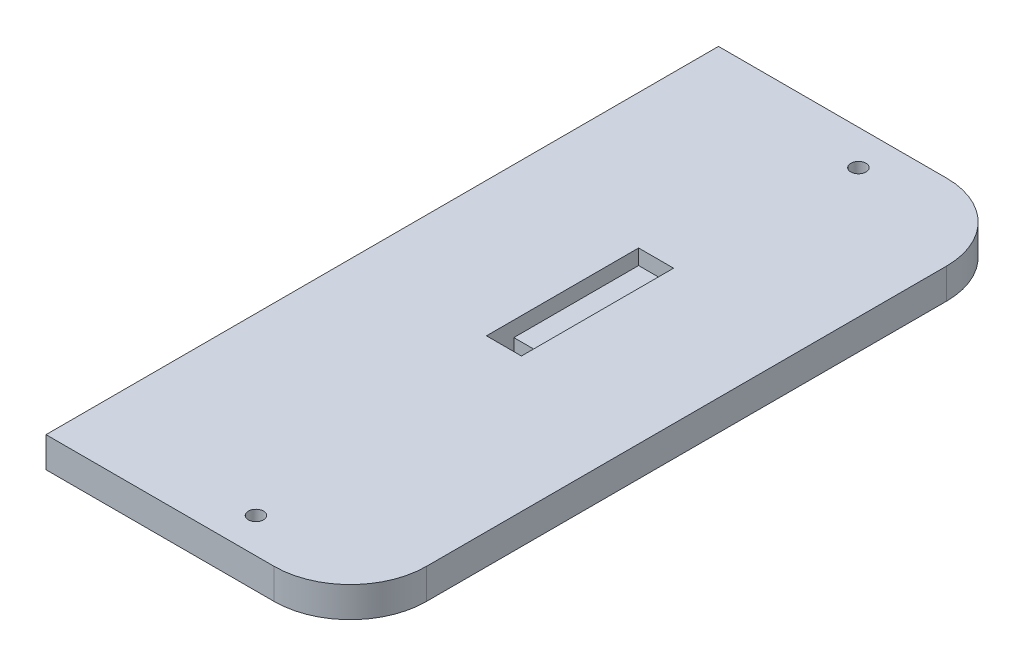
SolidWorks part; units mm, degrees
ref_plane "Front Plane" through (0, 0, 0) normal (0, 0, 1) x (1, 0, 0)
ref_plane "Top Plane" through (0, 0, 0) normal (0, 1, 0) x (1, 0, 0)
ref_plane "Right Plane" through (0, 0, 0) normal (1, 0, 0) x (0, 0, -1)
sketch "Sketch1" plane through (0, 0, 0) normal (0, 1, 0) x (1, 0, 0)
  line L1 (0, 0) -> (40, 0)
  line L2 (0, 0) -> (0, 88.4)
  line L3 (0, 88.4) -> (40, 88.4)
  line L4 (40, 0) -> (40, 88.4)
  dimension "D1" = 40
  dimension "D2" = 88.4
extrude "Boss-Extrude1" add sketch "Sketch1" along normal blind 4
fillet "Fillet1" radius 10 2 edges at (40, 2, -88.4) (40, 2, 0)
sketch "Sketch3" plane through (0, 0, 0) normal (0, -1, 0) x (1, 0, 0)
  line L0 (0, 0) -> (30, 0) construction
  line L1 (30, -88.4) -> (0, -88.4) construction
  circle A0 centre (23, -4.6) radius 1
  circle A1 centre (23, -83.8) radius 1
  point P6 (15, 0)
  point P9 (15, -88.4)
  dimension "D1" = 4.6
  dimension "D2" = 8
  dimension "D3" = 4.6
  dimension "D4" = 8
extrude "Cut-Extrude1" cut sketch "Sketch3" against normal blind 10
sketch "Sketch5" plane through (0, 0, 0) normal (0, -1, 0) x (1, 0, 0)
  circle A0 centre (23, -4.6) radius 1.6
  circle A1 centre (23, -83.8) radius 1.6
extrude "Cut-Extrude2" cut sketch "Sketch5" against normal blind 2.5
sketch "Sketch6" plane through (0, 0, 0) normal (0, -1, 0) x (1, 0, 0)
  line L0 (0, -88.4) -> (0, 0) construction
  line L1 (17.7, -40.2) -> (22.3, -40.2)
  line L2 (17.7, -40.2) -> (17.7, -60.2)
  line L3 (17.7, -60.2) -> (22.3, -60.2)
  line L4 (22.3, -40.2) -> (22.3, -60.2)
  line L6 (40, -10) -> (40, -78.4) construction
  point P6 (0, -44.2)
  dimension "D1" = 20
  dimension "D2" = 4.6
  dimension "D3" = 4
  dimension "D4" = 17.7
extrude "Cut-Extrude3" cut sketch "Sketch6" along direction (0, -1, 0) on the side against the normal blind 10 from offset 2 offset against normal yes
sketch "Sketch8" plane through (0, 2, 0) normal (0, 1, 0) x (1, 0, 0)
  line L0 (22.3, 60.2) -> (22.3, 40.2) construction
  line L1 (17.7, 40.2) -> (22.3, 40.2)
  line L2 (17.7, 40.2) -> (17.7, 43.8)
  line L3 (17.7, 43.8) -> (22.3, 43.8)
  line L4 (22.3, 40.2) -> (22.3, 43.8)
  dimension "D1" = 3.6
extrude "Cut-Extrude7" cut sketch "Sketch8" against normal blind 11.5
